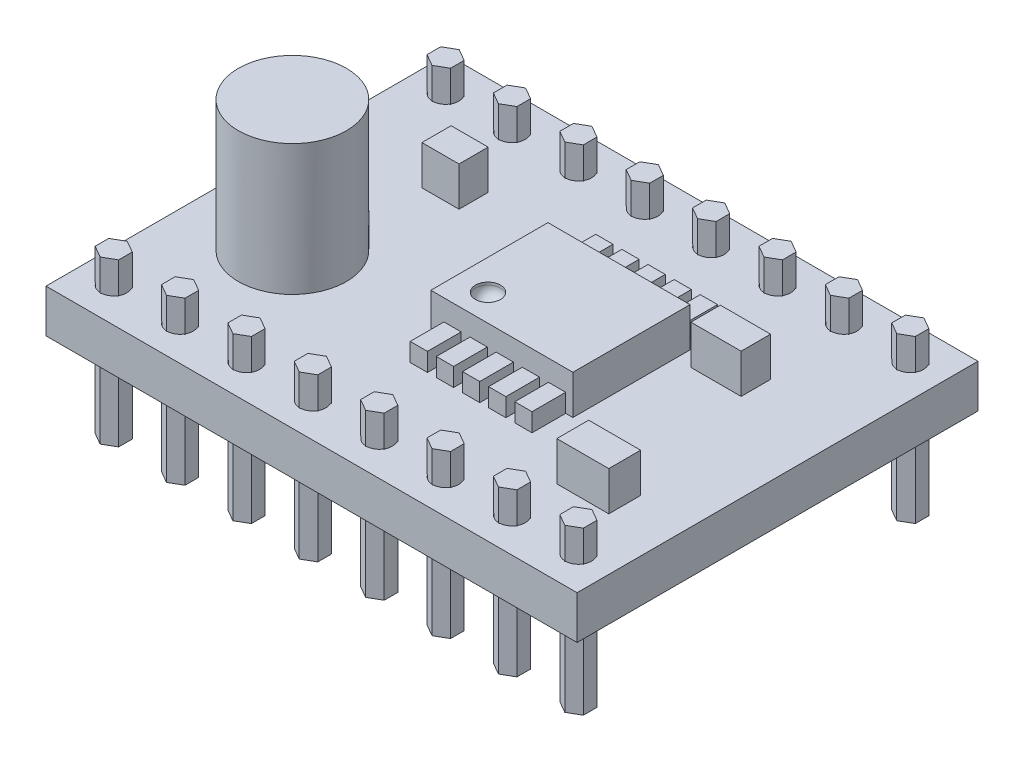
SolidWorks part; units mm, degrees
ref_plane "Front Plane" through (0, 0, 0) normal (0, 0, 1) x (1, 0, 0)
ref_plane "Top Plane" through (0, 0, 0) normal (0, 1, 0) x (1, 0, 0)
ref_plane "Right Plane" through (0, 0, 0) normal (1, 0, 0) x (0, 0, -1)
sketch "Sketch1" plane through (0, 0, 0) normal (0, 1, 0) x (1, 0, 0)
  line L0 (0, 0) -> (0, 7.67) construction
  line L1 (-10.16, -7.67) -> (10.16, -7.67)
  line L2 (-10.16, -7.67) -> (-10.16, 7.67)
  line L3 (-10.16, 7.67) -> (10.16, 7.67)
  line L4 (10.16, -7.67) -> (10.16, 7.67)
  line L5 (-10.16, -7.67) -> (10.16, 7.67) construction
  line L6 (-10.16, 7.67) -> (10.16, -7.67) construction
  line L7 (0, 0) -> (-6.35, 0) construction
  circle A0 centre (1.27, 6.35) radius 0.5
  circle A1 centre (3.81, 6.35) radius 0.5
  circle A2 centre (6.35, 6.35) radius 0.5
  circle A3 centre (8.89, 6.35) radius 0.5
  circle A4 centre (-1.27, 6.35) radius 0.5
  circle A5 centre (-3.81, 6.35) radius 0.5
  circle A6 centre (-6.35, 6.35) radius 0.5
  circle A7 centre (-8.89, 6.35) radius 0.5
  circle A12 centre (-8.89, -6.35) radius 0.5
  circle A13 centre (-8.89, -3.81) radius 0.5 [skipped]
  circle A14 centre (-8.89, -1.27) radius 0.5 [skipped]
  circle A15 centre (-8.89, 1.27) radius 0.5 [skipped]
  circle A16 centre (-8.89, 3.81) radius 0.5 [skipped]
  circle A17 centre (-6.35, -6.35) radius 0.5
  circle A18 centre (-3.81, -6.35) radius 0.5
  circle A19 centre (-1.27, -6.35) radius 0.5
  circle A20 centre (1.27, -6.35) radius 0.5
  circle A21 centre (3.81, -6.35) radius 0.5
  circle A22 centre (6.35, -6.35) radius 0.5
  circle A23 centre (8.89, -6.35) radius 0.5
  point P0 (0, 0)
  dimension "D3" = 1
  dimension "D1" = 20.32
  dimension "D2" = 15.34
  dimension "D4" = 8.89
  dimension "D5" = 6.35
  dimension "D8" = 17.78
  dimension "D10" = 12.7
  dimension "D6" = 4
  dimension "D7" = 5
  dimension "D9" = 6
  dimension "D11" = 8
extrude "Boss-Extrude1" add sketch "Sketch1" along normal blind 1.65
sketch "Sketch2" plane through (0, 1.65, 0) normal (0, 1, 0) x (1, 0, 0)
  line L1 (-1.16, -1.9459) -> (4.2755, -1.9459)
  line L2 (-1.16, -1.9459) -> (-1.16, 2.5355)
  line L3 (-1.16, 2.5355) -> (4.2755, 2.5355)
  line L4 (4.2755, -1.9459) -> (4.2755, 2.5355)
  line L5 (-1.16, -1.9459) -> (4.2755, 2.5355) construction
  line L6 (-1.16, 2.5355) -> (4.2755, -1.9459) construction
  line L7 (6.1647, -4.4508) -> (8.1533, -4.4508)
  line L8 (6.1647, -4.4508) -> (6.1647, -3.2315)
  line L9 (6.1647, -3.2315) -> (8.1533, -3.2315)
  line L10 (8.1533, -4.4508) -> (8.1533, -3.2315)
  line L11 (6.1647, -4.4508) -> (8.1533, -3.2315) construction
  line L12 (6.1647, -3.2315) -> (8.1533, -4.4508) construction
  line L13 (-6.2237, 2.7775) -> (-4.8058, 2.7775)
  line L14 (-6.2237, 2.7775) -> (-6.2237, 3.8943)
  line L15 (-6.2237, 3.8943) -> (-4.8058, 3.8943)
  line L16 (-4.8058, 2.7775) -> (-4.8058, 3.8943)
  line L17 (-6.2237, 2.7775) -> (-4.8058, 3.8943) construction
  line L18 (-6.2237, 3.8943) -> (-4.8058, 2.7775) construction
  line L19 (4.8721, 1.972) -> (6.7944, 1.972)
  line L20 (4.8721, 1.972) -> (4.8721, 3.0989)
  line L21 (4.8721, 3.0989) -> (6.7944, 3.0989)
  line L22 (6.7944, 1.972) -> (6.7944, 3.0989)
  line L23 (4.8721, 1.972) -> (6.7944, 3.0989) construction
  line L24 (4.8721, 3.0989) -> (6.7944, 1.972) construction
  circle A0 centre (-6.6287, -1.7732) radius 2.0679
  point P2 (1.5577, 0.2948)
  point P7 (7.159, -3.8411)
  point P12 (-5.5147, 3.3359)
  point P17 (5.8332, 2.5355)
extrude "Boss-Extrude2" add sketch "Sketch2" along normal blind 1.5
sketch "Sketch3" plane through (0, 3.15, 0) normal (0, 1, 0) x (1, 0, 0)
  circle A1 centre (-6.6287, -1.7732) radius 2.0679
  circle A2 centre (-6.6287, -1.7732) radius 2.0679
  dimension "D1" = 0
extrude "Boss-Extrude3" add sketch "Sketch3" along normal blind 3.5
sketch "Sketch4" plane through (0, 1.65, 0) normal (0, 1, 0) x (1, 0, 0)
  line L0 (-5.8995, 6.6101) -> (-6.35, 6.8702)
  line L1 (-8.4395, 6.6101) -> (-8.89, 6.8702)
  line L2 (-8.89, 6.8702) -> (-9.3405, 6.6101)
  line L3 (-9.3405, 6.6101) -> (-9.3405, 6.0899)
  line L4 (-9.3405, 6.0899) -> (-8.89, 5.8298)
  line L5 (-8.89, 5.8298) -> (-8.4395, 6.0899)
  line L6 (-8.4395, 6.0899) -> (-8.4395, 6.6101)
  line L7 (-6.35, 6.8702) -> (-6.8005, 6.6101)
  line L8 (-10.16, 7.67) -> (-10.16, -7.67) construction
  line L9 (-6.8005, 6.6101) -> (-6.8005, 6.0899)
  line L10 (-6.8005, 6.0899) -> (-6.35, 5.8298)
  line L11 (-6.35, 5.8298) -> (-5.8995, 6.0899)
  line L12 (-5.8995, 6.0899) -> (-5.8995, 6.6101)
  line L13 (-3.3595, 6.6101) -> (-3.81, 6.8702)
  line L14 (-3.81, 6.8702) -> (-4.2605, 6.6101)
  line L15 (-4.2605, 6.6101) -> (-4.2605, 6.0899)
  line L16 (-4.2605, 6.0899) -> (-3.81, 5.8298)
  line L17 (-3.81, 5.8298) -> (-3.3595, 6.0899)
  line L18 (-3.3595, 6.0899) -> (-3.3595, 6.6101)
  line L19 (-0.8195, 6.6101) -> (-1.27, 6.8702)
  line L20 (-1.27, 6.8702) -> (-1.7205, 6.6101)
  line L21 (-1.7205, 6.6101) -> (-1.7205, 6.0899)
  line L22 (-1.7205, 6.0899) -> (-1.27, 5.8298)
  line L23 (-1.27, 5.8298) -> (-0.8195, 6.0899)
  line L24 (-0.8195, 6.0899) -> (-0.8195, 6.6101)
  line L25 (1.7205, 6.6101) -> (1.27, 6.8702)
  line L26 (1.27, 6.8702) -> (0.8195, 6.6101)
  line L27 (0.8195, 6.6101) -> (0.8195, 6.0899)
  line L28 (0.8195, 6.0899) -> (1.27, 5.8298)
  line L29 (1.27, 5.8298) -> (1.7205, 6.0899)
  line L30 (1.7205, 6.0899) -> (1.7205, 6.6101)
  line L31 (4.2605, 6.6101) -> (3.81, 6.8702)
  line L32 (3.81, 6.8702) -> (3.3595, 6.6101)
  line L33 (3.3595, 6.6101) -> (3.3595, 6.0899)
  line L34 (3.3595, 6.0899) -> (3.81, 5.8298)
  line L35 (3.81, 5.8298) -> (4.2605, 6.0899)
  line L36 (4.2605, 6.0899) -> (4.2605, 6.6101)
  line L37 (6.8005, 6.6101) -> (6.35, 6.8702)
  line L38 (6.35, 6.8702) -> (5.8995, 6.6101)
  line L39 (5.8995, 6.6101) -> (5.8995, 6.0899)
  line L40 (5.8995, 6.0899) -> (6.35, 5.8298)
  line L41 (6.35, 5.8298) -> (6.8005, 6.0899)
  line L42 (6.8005, 6.0899) -> (6.8005, 6.6101)
  line L43 (9.3405, 6.6101) -> (8.89, 6.8702)
  line L44 (8.89, 6.8702) -> (8.4395, 6.6101)
  line L45 (8.4395, 6.6101) -> (8.4395, 6.0899)
  line L46 (8.4395, 6.0899) -> (8.89, 5.8298)
  line L47 (8.89, 5.8298) -> (9.3405, 6.0899)
  line L48 (9.3405, 6.0899) -> (9.3405, 6.6101)
  line L49 (-5.8995, -6.0899) -> (-6.35, -5.8298)
  line L50 (-6.35, -5.8298) -> (-6.8005, -6.0899)
  line L51 (-6.8005, -6.0899) -> (-6.8005, -6.6101)
  line L52 (-6.8005, -6.6101) -> (-6.35, -6.8702)
  line L53 (-6.35, -6.8702) -> (-5.8995, -6.6101)
  line L54 (-5.8995, -6.6101) -> (-5.8995, -6.0899)
  line L55 (-3.3595, -6.0899) -> (-3.81, -5.8298)
  line L56 (-3.81, -5.8298) -> (-4.2605, -6.0899)
  line L57 (-4.2605, -6.0899) -> (-4.2605, -6.6101)
  line L58 (-4.2605, -6.6101) -> (-3.81, -6.8702)
  line L59 (-3.81, -6.8702) -> (-3.3595, -6.6101)
  line L60 (-3.3595, -6.6101) -> (-3.3595, -6.0899)
  line L61 (-0.8195, -6.0899) -> (-1.27, -5.8298)
  line L62 (-1.27, -5.8298) -> (-1.7205, -6.0899)
  line L63 (-1.7205, -6.0899) -> (-1.7205, -6.6101)
  line L64 (-1.7205, -6.6101) -> (-1.27, -6.8702)
  line L65 (-1.27, -6.8702) -> (-0.8195, -6.6101)
  line L66 (-0.8195, -6.6101) -> (-0.8195, -6.0899)
  line L67 (1.7205, -6.0899) -> (1.27, -5.8298)
  line L68 (1.27, -5.8298) -> (0.8195, -6.0899)
  line L69 (0.8195, -6.0899) -> (0.8195, -6.6101)
  line L70 (0.8195, -6.6101) -> (1.27, -6.8702)
  line L71 (1.27, -6.8702) -> (1.7205, -6.6101)
  line L72 (1.7205, -6.6101) -> (1.7205, -6.0899)
  line L73 (4.2605, -6.0899) -> (3.81, -5.8298)
  line L74 (3.81, -5.8298) -> (3.3595, -6.0899)
  line L75 (3.3595, -6.0899) -> (3.3595, -6.6101)
  line L76 (3.3595, -6.6101) -> (3.81, -6.8702)
  line L77 (3.81, -6.8702) -> (4.2605, -6.6101)
  line L78 (4.2605, -6.6101) -> (4.2605, -6.0899)
  line L79 (6.8005, -6.0899) -> (6.35, -5.8298)
  line L80 (6.35, -5.8298) -> (5.8995, -6.0899)
  line L81 (5.8995, -6.0899) -> (5.8995, -6.6101)
  line L82 (5.8995, -6.6101) -> (6.35, -6.8702)
  line L83 (6.35, -6.8702) -> (6.8005, -6.6101)
  line L84 (6.8005, -6.6101) -> (6.8005, -6.0899)
  line L85 (9.3405, -6.0899) -> (8.89, -5.8298)
  line L86 (8.89, -5.8298) -> (8.4395, -6.0899)
  line L87 (8.4395, -6.0899) -> (8.4395, -6.6101)
  line L88 (8.4395, -6.6101) -> (8.89, -6.8702)
  line L89 (8.89, -6.8702) -> (9.3405, -6.6101)
  line L90 (9.3405, -6.6101) -> (9.3405, -6.0899)
  line L91 (-8.4395, -6.0899) -> (-8.89, -5.8298)
  line L92 (-8.89, -5.8298) -> (-9.3405, -6.0899)
  line L93 (-9.3405, -6.0899) -> (-9.3405, -6.6101)
  line L94 (-9.3405, -6.6101) -> (-8.89, -6.8702)
  line L95 (-8.89, -6.8702) -> (-8.4395, -6.6101)
  line L96 (-8.4395, -6.6101) -> (-8.4395, -6.0899)
  circle A0 centre (-8.89, 6.35) radius 0.4505 construction
  circle A1 centre (-6.35, 6.35) radius 0.4505 construction
  circle A2 centre (-3.81, 6.35) radius 0.4505 construction
  circle A3 centre (-1.27, 6.35) radius 0.4505 construction
  circle A4 centre (1.27, 6.35) radius 0.4505 construction
  circle A5 centre (3.81, 6.35) radius 0.4505 construction
  circle A6 centre (6.35, 6.35) radius 0.4505 construction
  circle A7 centre (8.89, 6.35) radius 0.4505 construction
  circle A8 centre (-6.35, -6.35) radius 0.4505 construction
  circle A9 centre (-3.81, -6.35) radius 0.4505 construction
  circle A10 centre (-1.27, -6.35) radius 0.4505 construction
  circle A11 centre (1.27, -6.35) radius 0.4505 construction
  circle A12 centre (3.81, -6.35) radius 0.4505 construction
  circle A13 centre (6.35, -6.35) radius 0.4505 construction
  circle A14 centre (8.89, -6.35) radius 0.4505 construction
  circle A15 centre (-8.89, -6.35) radius 0.4505 construction
  dimension "D1" = 8
  dimension "D2" = 2
extrude "Boss-Extrude4" add sketch "Sketch4" along normal blind 1.2 and the other way blind 5
sketch "Sketch5" plane through (0, 1.65, 0) normal (0, 1, 0) x (1, 0, 0)
  line L0 (4.2755, 2.5355) -> (-1.16, 2.5355) construction
  line L1 (-0.66, 3.8644) -> (0, 3.8644)
  line L2 (-0.66, 3.8644) -> (-0.66, 2.5355)
  line L3 (-0.66, 2.5355) -> (0, 2.5355)
  line L4 (0, 3.8644) -> (0, 2.5355)
  line L5 (0.34, 3.8644) -> (1, 3.8644)
  line L6 (0.34, 3.8644) -> (0.34, 2.5355)
  line L7 (0.34, 2.5355) -> (1, 2.5355)
  line L8 (1, 3.8644) -> (1, 2.5355)
  line L9 (1.34, 3.8644) -> (2, 3.8644)
  line L10 (1.34, 3.8644) -> (1.34, 2.5355)
  line L11 (1.34, 2.5355) -> (2, 2.5355)
  line L12 (2, 3.8644) -> (2, 2.5355)
  line L13 (2.34, 3.8644) -> (3, 3.8644)
  line L14 (2.34, 3.8644) -> (2.34, 2.5355)
  line L15 (2.34, 2.5355) -> (3, 2.5355)
  line L16 (3, 3.8644) -> (3, 2.5355)
  line L17 (3.34, 3.8644) -> (4, 3.8644)
  line L18 (3.34, 3.8644) -> (3.34, 2.5355)
  line L19 (3.34, 2.5355) -> (4, 2.5355)
  line L20 (4, 3.8644) -> (4, 2.5355)
  line L21 (0.34, -1.9056) -> (1, -1.9056)
  line L22 (0.34, -1.9056) -> (0.34, -3.2345)
  line L23 (0.34, -3.2345) -> (1, -3.2345)
  line L24 (1, -1.9056) -> (1, -3.2345)
  line L25 (1.34, -1.9056) -> (2, -1.9056)
  line L26 (1.34, -1.9056) -> (1.34, -3.2345)
  line L27 (1.34, -3.2345) -> (2, -3.2345)
  line L28 (2, -1.9056) -> (2, -3.2345)
  line L29 (2.34, -1.9056) -> (3, -1.9056)
  line L30 (2.34, -1.9056) -> (2.34, -3.2345)
  line L31 (2.34, -3.2345) -> (3, -3.2345)
  line L32 (3, -1.9056) -> (3, -3.2345)
  line L33 (3.34, -1.9056) -> (4, -1.9056)
  line L34 (3.34, -1.9056) -> (3.34, -3.2345)
  line L35 (3.34, -3.2345) -> (4, -3.2345)
  line L36 (4, -1.9056) -> (4, -3.2345)
  line L37 (-0.66, -1.9056) -> (0, -1.9056)
  line L38 (-0.66, -1.9056) -> (-0.66, -3.2345)
  line L39 (-0.66, -3.2345) -> (0, -3.2345)
  line L40 (0, -1.9056) -> (0, -3.2345)
  line L41 (-1.16, 2.5355) -> (-1.16, -1.9459) construction
  dimension "D3" = 0.5
  dimension "D1" = 5
  dimension "D2" = 2
extrude "Boss-Extrude5" add sketch "Sketch5" along normal blind 0.7
sketch "Sketch6" plane through (0, 3.15, 0) normal (0, 1, 0) x (1, 0, 0)
  circle A0 centre (0, -0.9193) radius 0.4777
  point P2 (0, -0.9193)
extrude "Cut-Extrude1" cut sketch "Sketch6" against normal blind 0.5
fillet "Fillet1" radius 0.4 1 edges at (0, 2.65, 1.3971)
